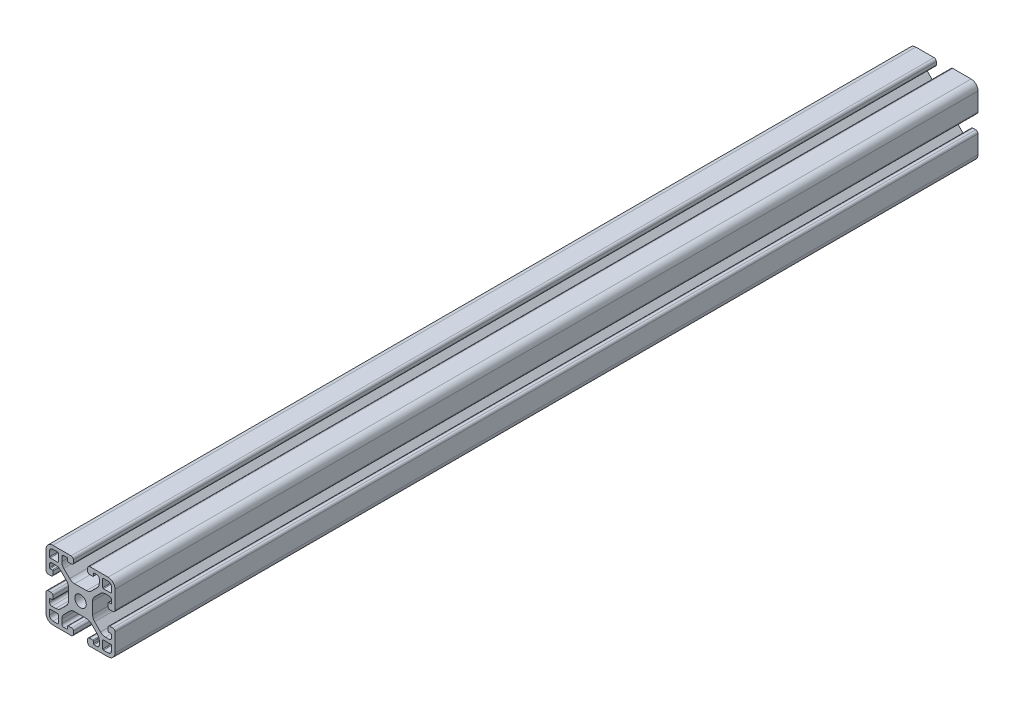
SolidWorks part; units mm, degrees
ref_plane "Plan de face" through (0, 0, 0) normal (0, 0, 1) x (1, 0, 0)
ref_plane "Plan de dessus" through (0, 0, 0) normal (0, 1, 0) x (1, 0, 0)
ref_plane "Plan de droite" through (0, 0, 0) normal (1, 0, 0) x (0, 0, -1)
ref_plane "Plan1" through (0, 0, 20) normal (0, 0, 1) x (1, 0, 0)
sketch "Esquisse1" plane through (0, 0, 20) normal (0, 0, 1) x (1, 0, 0)
  line L0 (20.3, 3) -> (18.9, 3)
  line L1 (18.1, 2.2) -> (18.1, 1)
  line L2 (19.1, 0) -> (27, 0)
  line L3 (30, 3) -> (30, 10.9)
  line L4 (29, 11.9) -> (27.8, 11.9)
  line L5 (27, 11.1) -> (27, 9.7)
  line L6 (27.3, 9.4) -> (28.2, 9.4)
  line L7 (28.5, 9.1) -> (28.5, 7.85)
  line L8 (27.5, 6.85) -> (25.8069, 6.85)
  line L9 (23.6855, 7.7287) -> (21.1287, 10.2855)
  line L10 (20.25, 12.4069) -> (20.25, 17.5931)
  line L11 (21.1287, 19.7145) -> (23.6855, 22.2713)
  line L12 (25.8069, 23.15) -> (27.5, 23.15)
  line L13 (28.5, 22.15) -> (28.5, 20.9)
  line L14 (28.2, 20.6) -> (27.3, 20.6)
  line L15 (27, 20.3) -> (27, 18.9)
  line L16 (27.8, 18.1) -> (29, 18.1)
  line L17 (30, 19.1) -> (30, 27)
  line L18 (27, 30) -> (19.1, 30)
  line L19 (18.1, 29) -> (18.1, 27.8)
  line L20 (18.9, 27) -> (20.3, 27)
  line L21 (20.6, 27.3) -> (20.6, 28.2)
  line L22 (20.9, 28.5) -> (22.15, 28.5)
  line L23 (23.15, 27.5) -> (23.15, 25.8069)
  line L24 (22.2713, 23.6855) -> (19.7145, 21.1287)
  line L25 (17.5931, 20.25) -> (12.4069, 20.25)
  line L26 (10.2855, 21.1287) -> (7.7287, 23.6855)
  line L27 (6.85, 25.8069) -> (6.85, 27.5)
  line L28 (7.85, 28.5) -> (9.1, 28.5)
  line L29 (9.4, 28.2) -> (9.4, 27.3)
  line L30 (9.7, 27) -> (11.1, 27)
  line L31 (11.9, 27.8) -> (11.9, 29)
  line L32 (10.9, 30) -> (3, 30)
  line L33 (0, 27) -> (0, 19.1)
  line L34 (1, 18.1) -> (2.2, 18.1)
  line L35 (3, 18.9) -> (3, 20.3)
  line L36 (2.7, 20.6) -> (1.8, 20.6)
  line L37 (1.5, 20.9) -> (1.5, 22.15)
  line L38 (2.5, 23.15) -> (4.1931, 23.15)
  line L39 (6.3145, 22.2713) -> (8.8713, 19.7145)
  line L40 (9.75, 17.5931) -> (9.75, 12.4069)
  line L41 (8.8713, 10.2855) -> (6.3145, 7.7287)
  line L42 (4.1931, 6.85) -> (2.5, 6.85)
  line L43 (1.5, 7.85) -> (1.5, 9.1)
  line L44 (1.8, 9.4) -> (2.7, 9.4)
  line L45 (3, 9.7) -> (3, 11.1)
  line L46 (2.2, 11.9) -> (1, 11.9)
  line L47 (0, 10.9) -> (0, 3)
  line L48 (3, 0) -> (10.9, 0)
  line L49 (11.9, 1) -> (11.9, 2.2)
  line L50 (11.1, 3) -> (9.7, 3)
  line L51 (9.4, 2.7) -> (9.4, 1.8)
  line L52 (9.1, 1.5) -> (7.85, 1.5)
  line L53 (6.85, 2.5) -> (6.85, 4.1931)
  line L54 (7.7287, 6.3145) -> (10.2855, 8.8713)
  line L55 (12.4069, 9.75) -> (17.5931, 9.75)
  line L56 (19.7145, 8.8713) -> (22.2713, 6.3145)
  line L57 (23.15, 4.1931) -> (23.15, 2.5)
  line L58 (22.15, 1.5) -> (20.9, 1.5)
  line L59 (20.6, 1.8) -> (20.6, 2.7)
  line L60 (5.35, 5.05) -> (5.35, 1.8)
  line L61 (5.05, 1.5) -> (3, 1.5)
  line L62 (1.5, 3) -> (1.5, 5.05)
  line L63 (1.8, 5.35) -> (5.05, 5.35)
  line L64 (24.95, 5.35) -> (28.2, 5.35)
  line L65 (28.5, 5.05) -> (28.5, 3)
  line L66 (27, 1.5) -> (24.95, 1.5)
  line L67 (24.65, 1.8) -> (24.65, 5.05)
  line L68 (24.65, 24.95) -> (24.65, 28.2)
  line L69 (24.95, 28.5) -> (27, 28.5)
  line L70 (28.5, 27) -> (28.5, 24.95)
  line L71 (28.2, 24.65) -> (24.95, 24.65)
  line L72 (5.05, 24.65) -> (1.8, 24.65)
  line L73 (1.5, 24.95) -> (1.5, 27)
  line L74 (3, 28.5) -> (5.05, 28.5)
  line L75 (5.35, 28.2) -> (5.35, 24.95)
  arc A0 (20.6, 2.7) -> (20.3, 3) centre (20.3, 2.7) ccw
  arc A1 (18.9, 3) -> (18.1, 2.2) centre (18.9, 2.2) ccw
  arc A2 (18.1, 1) -> (19.1, 0) centre (19.1, 1) ccw
  arc A3 (27, 0) -> (30, 3) centre (27, 3) ccw
  arc A4 (30, 10.9) -> (29, 11.9) centre (29, 10.9) ccw
  arc A5 (27.8, 11.9) -> (27, 11.1) centre (27.8, 11.1) ccw
  arc A6 (27, 9.7) -> (27.3, 9.4) centre (27.3, 9.7) ccw
  arc A7 (28.2, 9.4) -> (28.5, 9.1) centre (28.2, 9.1) cw
  arc A8 (28.5, 7.85) -> (27.5, 6.85) centre (27.5, 7.85) cw
  arc A9 (25.8069, 6.85) -> (23.6855, 7.7287) centre (25.8069, 9.85) cw
  arc A10 (21.1287, 10.2855) -> (20.25, 12.4069) centre (23.25, 12.4069) cw
  arc A11 (20.25, 17.5931) -> (21.1287, 19.7145) centre (23.25, 17.5931) cw
  arc A12 (23.6855, 22.2713) -> (25.8069, 23.15) centre (25.8069, 20.15) cw
  arc A13 (27.5, 23.15) -> (28.5, 22.15) centre (27.5, 22.15) cw
  arc A14 (28.5, 20.9) -> (28.2, 20.6) centre (28.2, 20.9) cw
  arc A15 (27.3, 20.6) -> (27, 20.3) centre (27.3, 20.3) ccw
  arc A16 (27, 18.9) -> (27.8, 18.1) centre (27.8, 18.9) ccw
  arc A17 (29, 18.1) -> (30, 19.1) centre (29, 19.1) ccw
  arc A18 (30, 27) -> (27, 30) centre (27, 27) ccw
  arc A19 (19.1, 30) -> (18.1, 29) centre (19.1, 29) ccw
  arc A20 (18.1, 27.8) -> (18.9, 27) centre (18.9, 27.8) ccw
  arc A21 (20.3, 27) -> (20.6, 27.3) centre (20.3, 27.3) ccw
  arc A22 (20.6, 28.2) -> (20.9, 28.5) centre (20.9, 28.2) cw
  arc A23 (22.15, 28.5) -> (23.15, 27.5) centre (22.15, 27.5) cw
  arc A24 (23.15, 25.8069) -> (22.2713, 23.6855) centre (20.15, 25.8069) cw
  arc A25 (19.7145, 21.1287) -> (17.5931, 20.25) centre (17.5931, 23.25) cw
  arc A26 (12.4069, 20.25) -> (10.2855, 21.1287) centre (12.4069, 23.25) cw
  arc A27 (7.7287, 23.6855) -> (6.85, 25.8069) centre (9.85, 25.8069) cw
  arc A28 (6.85, 27.5) -> (7.85, 28.5) centre (7.85, 27.5) cw
  arc A29 (9.1, 28.5) -> (9.4, 28.2) centre (9.1, 28.2) cw
  arc A30 (9.4, 27.3) -> (9.7, 27) centre (9.7, 27.3) ccw
  arc A31 (11.1, 27) -> (11.9, 27.8) centre (11.1, 27.8) ccw
  arc A32 (11.9, 29) -> (10.9, 30) centre (10.9, 29) ccw
  arc A33 (3, 30) -> (0, 27) centre (3, 27) ccw
  arc A34 (0, 19.1) -> (1, 18.1) centre (1, 19.1) ccw
  arc A35 (2.2, 18.1) -> (3, 18.9) centre (2.2, 18.9) ccw
  arc A36 (3, 20.3) -> (2.7, 20.6) centre (2.7, 20.3) ccw
  arc A37 (1.8, 20.6) -> (1.5, 20.9) centre (1.8, 20.9) cw
  arc A38 (1.5, 22.15) -> (2.5, 23.15) centre (2.5, 22.15) cw
  arc A39 (4.1931, 23.15) -> (6.3145, 22.2713) centre (4.1931, 20.15) cw
  arc A40 (8.8713, 19.7145) -> (9.75, 17.5931) centre (6.75, 17.5931) cw
  arc A41 (9.75, 12.4069) -> (8.8713, 10.2855) centre (6.75, 12.4069) cw
  arc A42 (6.3145, 7.7287) -> (4.1931, 6.85) centre (4.1931, 9.85) cw
  arc A43 (2.5, 6.85) -> (1.5, 7.85) centre (2.5, 7.85) cw
  arc A44 (1.5, 9.1) -> (1.8, 9.4) centre (1.8, 9.1) cw
  arc A45 (2.7, 9.4) -> (3, 9.7) centre (2.7, 9.7) ccw
  arc A46 (3, 11.1) -> (2.2, 11.9) centre (2.2, 11.1) ccw
  arc A47 (1, 11.9) -> (0, 10.9) centre (1, 10.9) ccw
  arc A48 (0, 3) -> (3, 0) centre (3, 3) ccw
  arc A49 (10.9, 0) -> (11.9, 1) centre (10.9, 1) ccw
  arc A50 (11.9, 2.2) -> (11.1, 3) centre (11.1, 2.2) ccw
  arc A51 (9.7, 3) -> (9.4, 2.7) centre (9.7, 2.7) ccw
  arc A52 (9.4, 1.8) -> (9.1, 1.5) centre (9.1, 1.8) cw
  arc A53 (7.85, 1.5) -> (6.85, 2.5) centre (7.85, 2.5) cw
  arc A54 (6.85, 4.1931) -> (7.7287, 6.3145) centre (9.85, 4.1931) cw
  arc A55 (10.2855, 8.8713) -> (12.4069, 9.75) centre (12.4069, 6.75) cw
  arc A56 (17.5931, 9.75) -> (19.7145, 8.8713) centre (17.5931, 6.75) cw
  arc A57 (22.2713, 6.3145) -> (23.15, 4.1931) centre (20.15, 4.1931) cw
  arc A58 (23.15, 2.5) -> (22.15, 1.5) centre (22.15, 2.5) cw
  arc A59 (20.9, 1.5) -> (20.6, 1.8) centre (20.9, 1.8) cw
  circle A60 centre (15, 15) radius 2.5
  arc A61 (5.05, 5.35) -> (5.35, 5.05) centre (5.05, 5.05) cw
  arc A62 (5.35, 1.8) -> (5.05, 1.5) centre (5.05, 1.8) cw
  arc A63 (3, 1.5) -> (1.5, 3) centre (3, 3) cw
  arc A64 (1.5, 5.05) -> (1.8, 5.35) centre (1.8, 5.05) cw
  arc A65 (24.65, 5.05) -> (24.95, 5.35) centre (24.95, 5.05) cw
  arc A66 (28.2, 5.35) -> (28.5, 5.05) centre (28.2, 5.05) cw
  arc A67 (28.5, 3) -> (27, 1.5) centre (27, 3) cw
  arc A68 (24.95, 1.5) -> (24.65, 1.8) centre (24.95, 1.8) cw
  arc A69 (24.95, 24.65) -> (24.65, 24.95) centre (24.95, 24.95) cw
  arc A70 (24.65, 28.2) -> (24.95, 28.5) centre (24.95, 28.2) cw
  arc A71 (27, 28.5) -> (28.5, 27) centre (27, 27) cw
  arc A72 (28.5, 24.95) -> (28.2, 24.65) centre (28.2, 24.95) cw
  arc A73 (5.35, 24.95) -> (5.05, 24.65) centre (5.05, 24.95) cw
  arc A74 (1.8, 24.65) -> (1.5, 24.95) centre (1.8, 24.95) cw
  arc A75 (1.5, 27) -> (3, 28.5) centre (3, 27) cw
  arc A76 (5.05, 28.5) -> (5.35, 28.2) centre (5.05, 28.2) cw
extrude "Boss.-Extru.1" add sketch "Esquisse1" against normal blind 375
